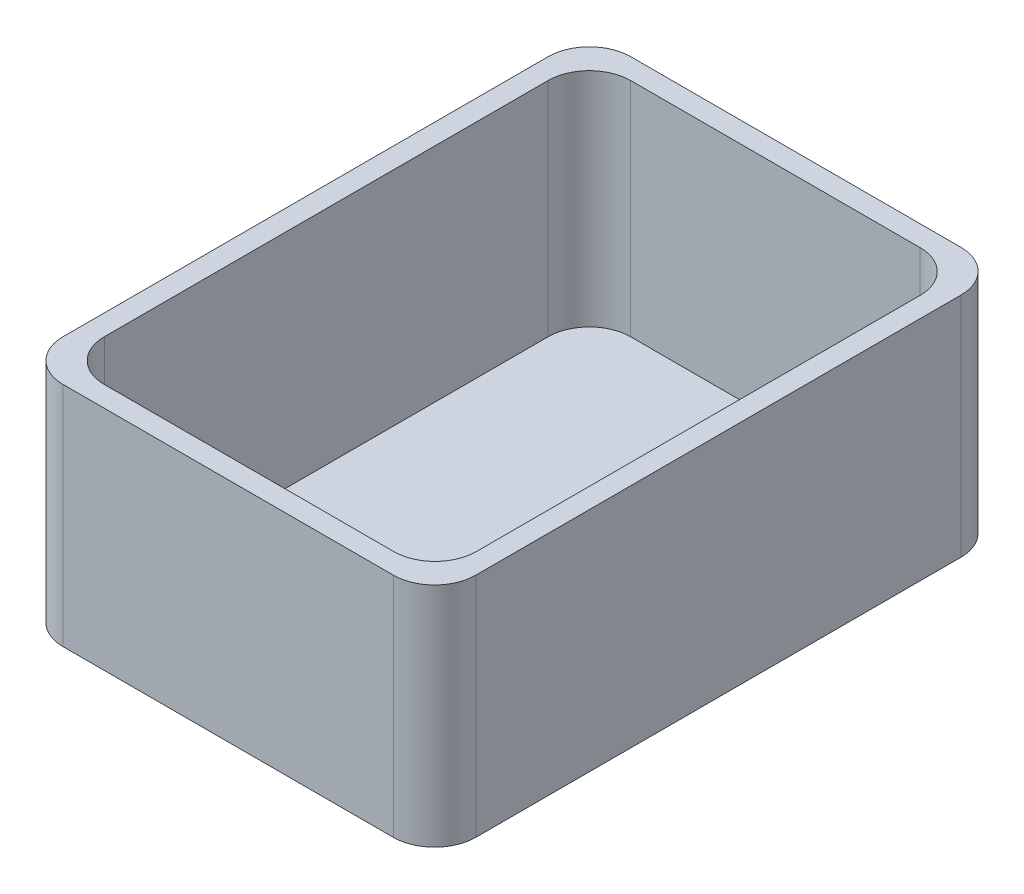
SolidWorks part; units mm, degrees
ref_plane "Front Plane" through (0, 0, 0) normal (0, 0, 1) x (1, 0, 0)
ref_plane "Top Plane" through (0, 0, 0) normal (0, 1, 0) x (1, 0, 0)
ref_plane "Right Plane" through (0, 0, 0) normal (1, 0, 0) x (0, 0, -1)
sketch "Sketch1" plane through (0, 0, 0) normal (0, 1, 0) x (1, 0, 0)
  line L1 (-200, 275) -> (200, 275)
  line L2 (-200, 275) -> (-200, -275)
  line L3 (-200, -275) -> (200, -275)
  line L4 (200, 275) -> (200, -275)
  line L5 (-200, 275) -> (200, -275) construction
  line L6 (-200, -275) -> (200, 275) construction
  point P0 (0, 0)
extrude "Boss-Extrude1" add sketch "Sketch1" along normal blind 220
sketch "Sketch2" plane through (0, 220, 0) normal (0, 1, 0) x (1, 0, 0)
  line L7 (-180, 254.9498) -> (180.4604, 254.9498)
  line L8 (-180, 254.9498) -> (-180, -255)
  line L9 (-180, -255) -> (180.4604, -255)
  line L10 (180.4604, 254.9498) -> (180.4604, -255)
  point P13 (0, 0)
extrude "Cut-Extrude1" cut sketch "Sketch2" against normal blind 215 contours L10 L7 L8 L9
fillet "Fillet2" radius 40 4 edges at (-200, 110, -275) (200, 110, -275) (-200, 110, 275) (200, 110, 275)
fillet "Fillet3" radius 40 4 edges at (180.4604, 112.5, -254.9498) (180.4604, 112.5, 255) (-180, 112.5, -254.9498) (-180, 112.5, 255)
